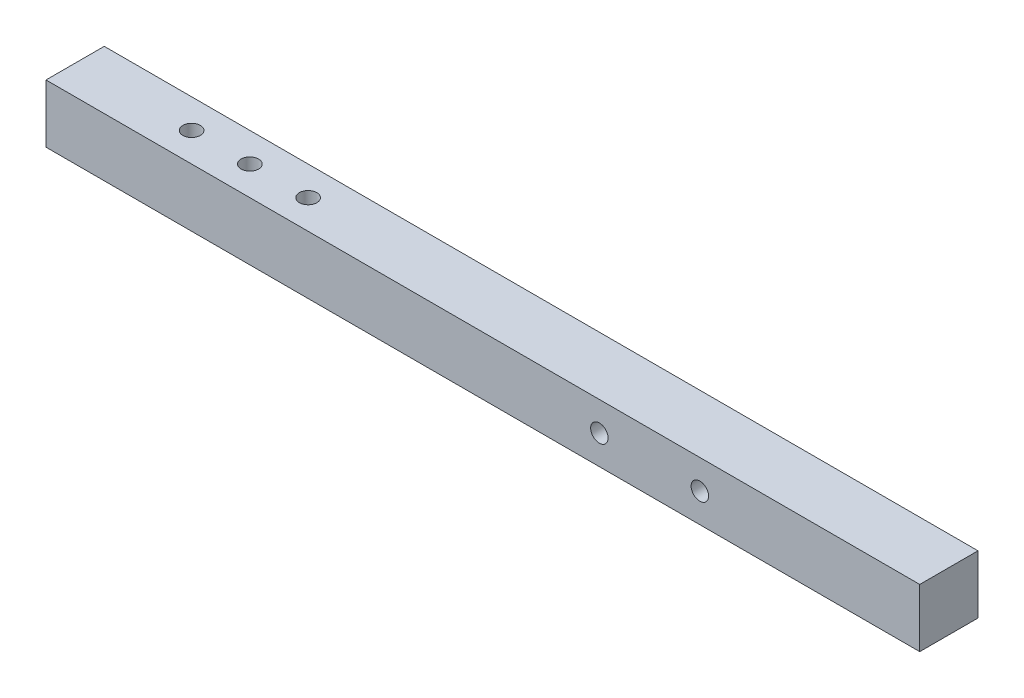
SolidWorks part; units mm, degrees
ref_plane "Front" through (0, 0, 0) normal (0, 0, 1) x (1, 0, 0)
ref_plane "Top" through (0, 0, 0) normal (0, 1, 0) x (1, 0, 0)
ref_plane "Right" through (0, 0, 0) normal (1, 0, 0) x (0, 0, -1)
sketch "Skizze1" plane through (0, 0, 0) normal (1, 0, 0) x (0, 0, -1)
  line L1 (-10, -10) -> (10, -10)
  line L2 (-10, -10) -> (-10, 10)
  line L3 (-10, 10) -> (10, 10)
  line L4 (10, -10) -> (10, 10)
  line L5 (-10, -10) -> (10, 10) construction
  line L6 (-10, 10) -> (10, -10) construction
  point P0 (0, 0)
  dimension "D1" = 20
extrude "Aufsatz-Linear austragen1" add sketch "Skizze1" along normal blind 300
sketch "Skizze2" plane through (0, 10, 0) normal (0, 1, 0) x (1, 0, 0)
  line L0 (0, 0) -> (300, 0) construction
  line L1 (0, 10) -> (0, -10) construction
  line L2 (300, 10) -> (300, -10) construction
  line L3 (150, 0) -> (150, 10) construction
  line L4 (300, 10) -> (0, 10) construction
  circle A0 centre (40, 0) radius 3
  circle A2 centre (60, 0) radius 3
  circle A3 centre (80, 0) radius 3
  dimension "D2" = 6
  dimension "D1" = 40
  dimension "D3" = 60
  dimension "D4" = 80
extrude "Schnitt-Linear austragen1" cut sketch "Skizze2" against normal through all
sketch "Sketch1" plane through (0, 0, 10) normal (0, 0, 1) x (1, 0, 0)
  line L0 (0, 0) -> (300, 0) construction
  line L1 (0, 10) -> (0, -10) construction
  line L2 (300, 10) -> (300, -10) construction
  circle A0 centre (190, 0) radius 3
  circle A1 centre (224.5, 0) radius 3
  dimension "D1" = 6
  dimension "D2" = 110
  dimension "D3" = 75.5
extrude "Extrude1" cut sketch "Sketch1" against normal through all
